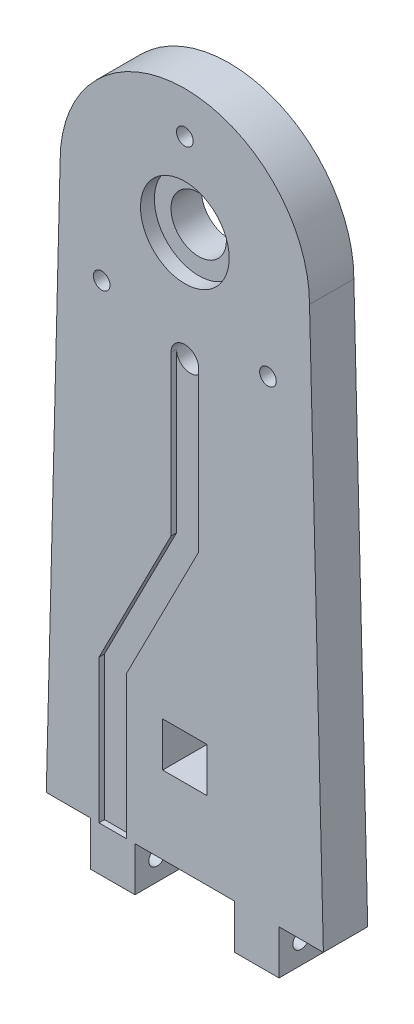
SolidWorks part; units mm, degrees
material "Acrylic (Medium-high impact)"
ref_plane "Front Plane" through (0, 0, 0) normal (0, 0, 1) x (1, 0, 0)
ref_plane "Top Plane" through (0, 0, 0) normal (0, 1, 0) x (1, 0, 0)
ref_plane "Right Plane" through (0, 0, 0) normal (1, 0, 0) x (0, 0, -1)
sketch "Sketch1" plane through (0, 0, 0) normal (0, 0, 1) x (1, 0, 0)
  line L0 (-22.5, 0) -> (-25, -100)
  line L1 (22.5, 0) -> (25, -100)
  line L2 (25, -100) -> (0, -100)
  line L3 (0, -100) -> (-25, -100)
  line L4 (0, 11.7595) -> (0, -124.9699) construction
  circle A0 centre (0, 0) radius 2.5 construction
  arc A1 (22.5, 0) -> (-22.5, 0) centre (0, 0) ccw
  dimension "D1" = 5
  dimension "D2" = 45
  dimension "D3" = 100
  dimension "D4" = 50
  dimension "D5" = 1.432
extrude "Arm Boss-Extrude1" add sketch "Sketch1" against normal blind 8
sketch "Sketch2" plane through (0, 0, 0) normal (0, 0, 1) x (1, 0, 0)
  circle A0 centre (0, 0) radius 8
  dimension "D1" = 16
extrude "Bearing Cut-Extrude1" cut sketch "Sketch2" against normal blind 2.5
sketch "Sketch3" plane through (0, 0, -2.5) normal (0, 0, 1) x (1, 0, 0)
  circle A0 centre (0, 0) radius 5
  dimension "D1" = 10
extrude "Shaft Hole Cut-Extrude2" cut sketch "Sketch3" against normal up to surface (5.5 mm away) up to face at (0, -44.375, -8)
sketch "Sketch4" plane through (0, 0, 0) normal (0, 0, 1) x (1, 0, 0)
  circle A0 centre (0, -20) radius 2.5
  dimension "D1" = 5
  dimension "D2" = 20
extrude "Cable Hole Cut-Extrude3" cut sketch "Sketch4" against normal up to surface (8 mm away) up to face at (5, 0, -8)
sketch "Sketch5" plane through (0, -100, 0) normal (0, -1, 0) x (1, 0, 0)
  line L0 (-25, 0) -> (25, 0) construction
  line L1 (-17, 0) -> (-9, 0)
  line L2 (-17, 0) -> (-17, -8)
  line L3 (-17, -8) -> (-9, -8)
  line L4 (-9, 0) -> (-9, -8)
  line L5 (-25, -8) -> (25, -8) construction
  line L6 (-25, -8) -> (-25, 0) construction
  line L7 (9, 0) -> (17, 0)
  line L8 (9, 0) -> (9, -8)
  line L9 (9, -8) -> (17, -8)
  line L10 (17, 0) -> (17, -8)
  line L11 (25, -8) -> (25, 0) construction
  dimension "D1" = 8
  dimension "D2" = 8
extrude "Puzzle Slot Boss-Extrude2" add sketch "Sketch5" along normal blind 8
sketch "Sketch6" plane through (0, 0, 0) normal (0, 0, 1) x (1, 0, 0)
  line L0 (-2.5, -20) -> (-2.5, -27.5)
  line L1 (2.5, -20) -> (2.5, -27.5)
  line L2 (2.5, -27.5) -> (-2.5, -27.5)
  line L3 (-2.5, -20) -> (2.5, -20)
  circle A0 centre (0, -20) radius 2.5 construction
  arc A1 (22.5, 0) -> (-22.5, 0) centre (0, 0) ccw construction
  point P6 (0, 22.5)
  dimension "D1" = 50
extrude "Cable Cut-Extrude4" cut sketch "Sketch6" against normal blind 1
sketch "Sketch7" plane through (0, 0, 0) normal (0, 0, 1) x (1, 0, 0)
  line L0 (0, 0) -> (0, 15) construction
  line L1 (-15, -15) -> (0, -15) construction
  line L2 (0, -15) -> (15, -15) construction
  line L3 (0, -15) -> (0, 0) construction
  circle A0 centre (-15, -15) radius 1.5
  circle A1 centre (15, -15) radius 1.5
  circle A2 centre (0, 15) radius 1.5
  dimension "D1" = 3
  dimension "D2" = 15
extrude "Mounting Holes Cut-Extrude5" cut sketch "Sketch7" against normal up to surface (8 mm away) up to face at (2.5, -20, -8)
sketch "Sketch8" plane through (-17, 0, 0) normal (-1, 0, 0) x (0, 0, 1)
  line L0 (-4, -100) -> (-4, -104) construction
  line L1 (-8, -100) -> (0, -100) construction
  line L2 (-4, -104) -> (-4, -108) construction
  line L3 (0, -108) -> (-8, -108) construction
  line L4 (-8, -104) -> (-4, -104) construction
  line L5 (-8, -108) -> (-8, -100) construction
  line L6 (-4, -104) -> (0, -104) construction
  line L7 (0, -108) -> (0, -100) construction
  circle A0 centre (-4, -104) radius 1.5
  dimension "D1" = 3
extrude "Puzzle Slot Screw Holes Cut-Extrude6" cut sketch "Sketch8" against normal up to surface (34 mm away) up to face at (17, -104, -4)
sketch "Sketch9" plane through (0, 0, 0) normal (0, 0, 1) x (1, 0, 0)
  line L0 (-4, -78) -> (0, -78)
  line L1 (0, -78) -> (4, -78)
  line L2 (-4, -78) -> (-4, -86)
  line L3 (-4, -86) -> (4, -86)
  line L4 (4, -78) -> (4, -86)
  line L5 (-9, -100) -> (9, -100) construction
  dimension "D1" = 8
  dimension "D2" = 22
extrude "Side Puzzle Slot Cut-Extrude7" cut sketch "Sketch9" against normal up to surface (8 mm away) up to face at (1.5, 15, -8)
sketch "Sketch10" plane through (0, 0, 0) normal (0, 0, 1) x (1, 0, 0)
  line L0 (-25, -100) -> (-17, -100) construction
  line L1 (-15.5, -100) -> (-10.5, -100)
  line L2 (-15.5, -100) -> (-15.5, -74.1177)
  line L4 (-10.5, -100) -> (-10.5, -74.1177)
  line L5 (-15.5, -74.1177) -> (-2.5, -48.6839)
  line L6 (-17, -108) -> (-17, -100) construction
  line L7 (-10.5, -74.1177) -> (2.5, -48.6839)
  line L9 (2.5, -27.5) -> (-2.5, -27.5)
  line L10 (2.5, -27.5) -> (2.5, -48.6839)
  line L12 (-2.5, -27.5) -> (-2.5, -48.6839)
  dimension "D1" = 5
  dimension "D2" = 1.5
extrude "Cable Lower Cut-Extrude8" cut sketch "Sketch10" against normal blind 1
